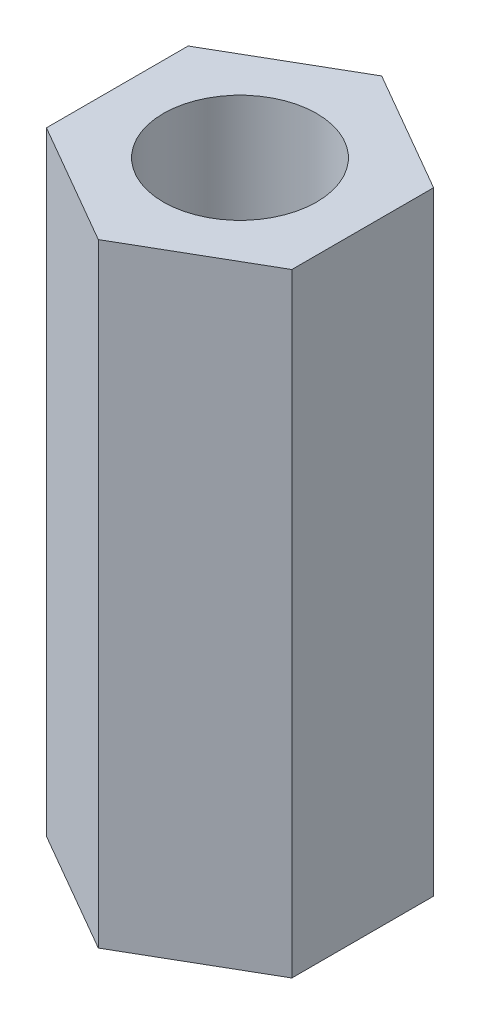
SolidWorks part; units mm, degrees
ref_plane "前视基准面" through (0, 0, 0) normal (0, 0, 1) x (1, 0, 0)
ref_plane "上视基准面" through (0, 0, 0) normal (0, 1, 0) x (1, 0, 0)
ref_plane "右视基准面" through (0, 0, 0) normal (1, 0, 0) x (0, 0, -1)
sketch "草图1" plane through (0, 0, 0) normal (0, 1, 0) x (1, 0, 0)
  line L1 (0, 4.6188) -> (-4, 2.3094)
  line L2 (-4, 2.3094) -> (-4, -2.3094)
  line L3 (-4, -2.3094) -> (0, -4.6188)
  line L4 (0, -4.6188) -> (4, -2.3094)
  line L5 (4, -2.3094) -> (4, 2.3094)
  line L6 (4, 2.3094) -> (0, 4.6188)
  circle A0 centre (0, 0) radius 4 construction
  circle A1 centre (0, 0) radius 2.5
  dimension "D1" = 5
  dimension "D2" = 8
extrude "凸台-拉伸1" add sketch "草图1" along normal blind 20
